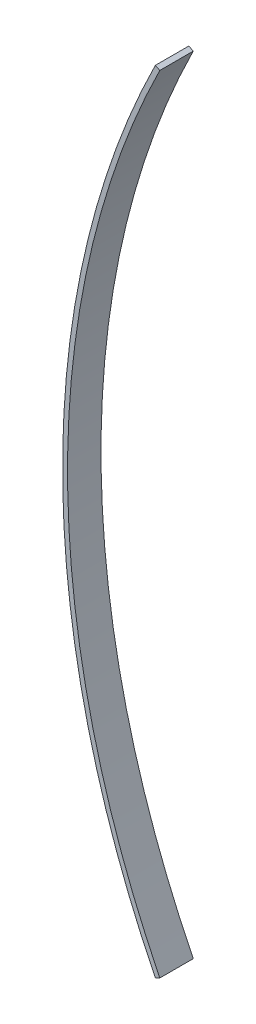
SolidWorks part; units mm, degrees
ref_plane "Front Plane" through (0, 0, 0) normal (0, 0, 1) x (1, 0, 0)
ref_plane "Top Plane" through (0, 0, 0) normal (0, 1, 0) x (1, 0, 0)
ref_plane "Right Plane" through (0, 0, 0) normal (1, 0, 0) x (0, 0, -1)
sketch "Sketch1" plane through (0, 0, 0) normal (0, 0, 1) x (1, 0, 0)
  arc B0 (18.6136, 163.5731) -> (18.6136, 4.963) centre (178.25, 84.268) ccw
  arc B1 (27.2098, 0) -> (164.5701, 79.305) centre (16.0718, 177.9017) ccw
  arc B2 (164.5701, 89.231) -> (27.2098, 168.5361) centre (16.0718, -9.3656) ccw
  circle B3 centre (70.1312, 84.268) radius 63.5
  circle B4 centre (70.1312, 84.268) radius 60
  circle B5 centre (70.1312, 84.268) radius 58.5
  circle B6 centre (70.1312, 84.268) radius 55
sketch_block_instance "sealsblock-1"
sketch_block "sealsblock"
extrude "Extrude-Thin1" add sketch "Sketch1" against normal blind 6.75 thin contours B0
